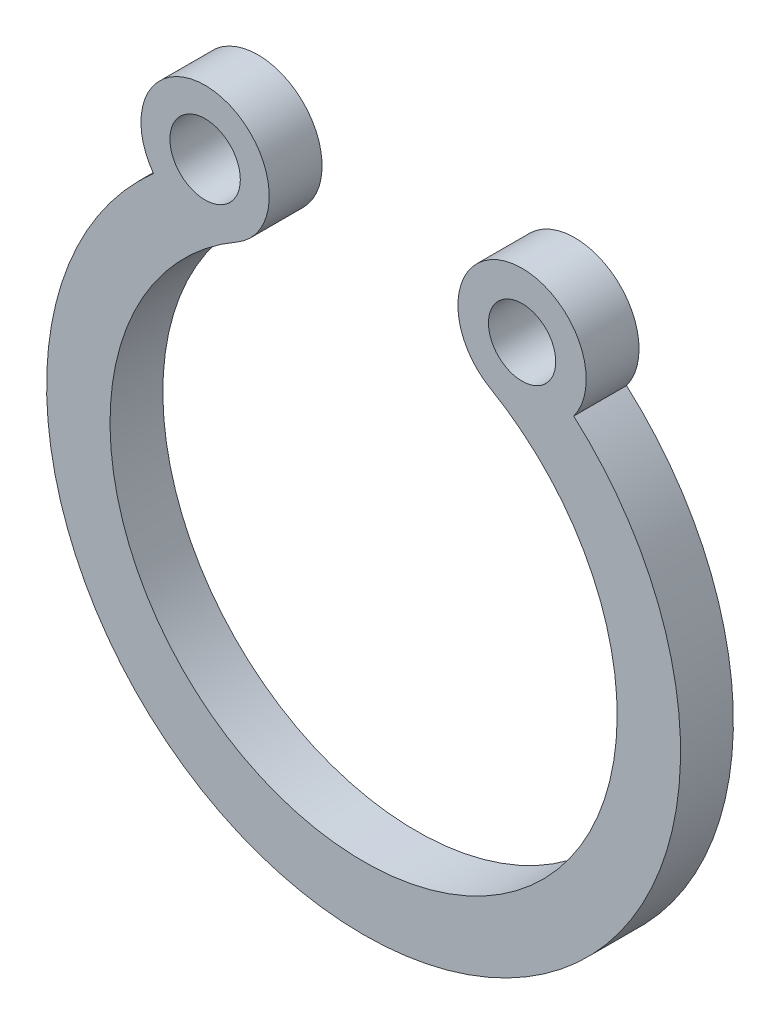
SolidWorks part; units mm, degrees
ref_plane "Plano frontal" through (0, 0, 0) normal (0, 0, 1) x (1, 0, 0)
ref_plane "Plano superior" through (0, 0, 0) normal (0, 1, 0) x (1, 0, 0)
ref_plane "Plano direito" through (0, 0, 0) normal (1, 0, 0) x (0, 0, -1)
sketch "Esboço1" plane through (0, 0, 0) normal (0, 0, 1) x (1, 0, 0)
  arc A0 (-2.3943, 4.1602) -> (2.3943, 4.1602) centre (0, 0) ccw
  arc A3 (-2.3943, 4.1602) -> (-3.9775, 4.4922) centre (-3, 5.2127) ccw
  arc A4 (3.9775, 4.4922) -> (2.3943, 4.1602) centre (3, 5.2127) ccw
  arc A6 (-3.9775, 4.4922) -> (3.9775, 4.4922) centre (0, 0) ccw
  dimension "D1" = 9.6
extrude "Ressalto-extrusão1" add sketch "Esboço1" along normal blind 1
sketch "Esboço2" plane through (0, 0, 1) normal (0, 0, 1) x (1, 0, 0)
  circle A0 centre (-3, 5.2127) radius 0.6667
  circle A1 centre (3, 5.2127) radius 0.6368
extrude "Corte-extrusão1" cut sketch "Esboço2" against normal blind 1
